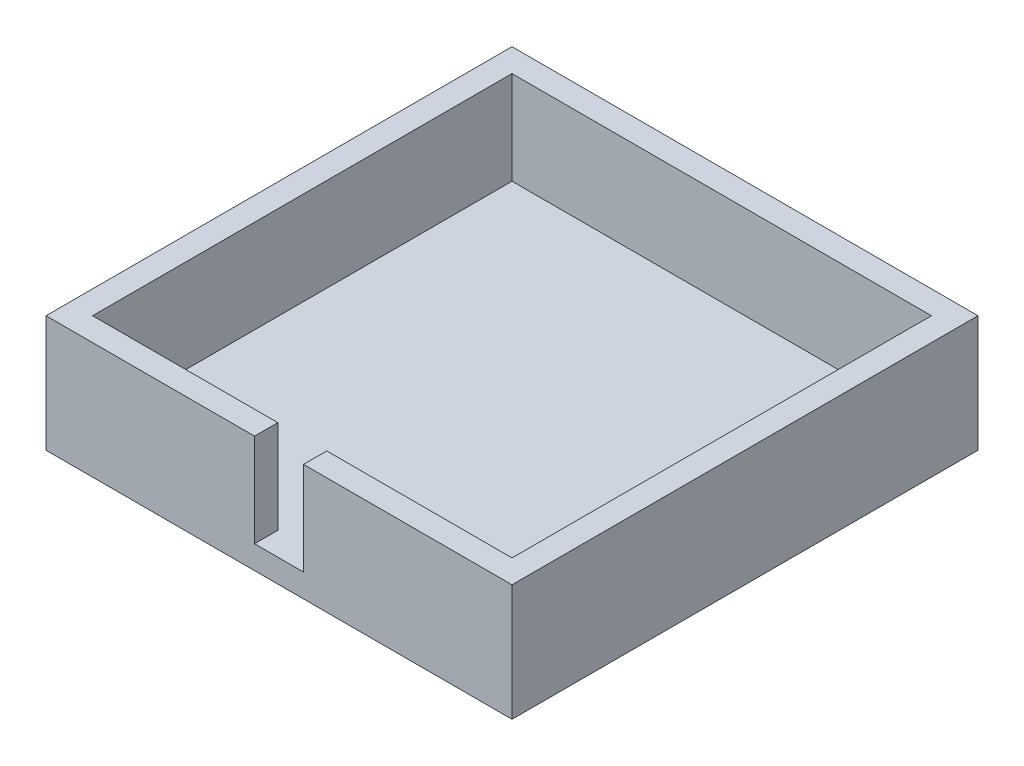
SolidWorks part; units mm, degrees
material "Plain Carbon Steel"
ref_plane "Front Plane" through (0, 0, 0) normal (0, 0, 1) x (1, 0, 0)
ref_plane "Top Plane" through (0, 0, 0) normal (0, 1, 0) x (1, 0, 0)
ref_plane "Right Plane" through (0, 0, 0) normal (1, 0, 0) x (0, 0, -1)
sketch "Sketch1" plane through (0, 0, 0) normal (0, 1, 0) x (1, 0, 0)
  line L1 (-100, -100) -> (100, -100)
  line L2 (-100, -100) -> (-100, 100)
  line L3 (-100, 100) -> (100, 100)
  line L4 (100, -100) -> (100, 100)
  line L5 (-100, -100) -> (100, 100) construction
  line L6 (-100, 100) -> (100, -100) construction
  point P0 (0, 0)
  dimension "D1" = 200
  dimension "D2" = 200
extrude "Boss-Extrude1" add sketch "Sketch1" along normal blind 50
sketch "Sketch2" plane through (0, 50, 0) normal (0, 1, 0) x (1, 0, 0)
  line L0 (100, 100) -> (-100, 100) construction
  line L1 (-90, -90) -> (90, -90)
  line L2 (-90, -90) -> (-90, 90)
  line L3 (-90, 90) -> (90, 90)
  line L4 (90, -90) -> (90, 90)
  line L5 (-90, -90) -> (90, 90) construction
  line L6 (-90, 90) -> (90, -90) construction
  line L7 (100, -100) -> (100, 100) construction
  point P0 (0, 0)
  dimension "D1" = 10
  dimension "D2" = 10
extrude "Cut-Extrude1" cut sketch "Sketch2" against normal blind 40 and the other way through all
sketch "Sketch3" plane through (0, 0, 100) normal (0, 0, 1) x (1, 0, 0)
  line L0 (-10.5, 10) -> (10.5, 10)
  line L1 (-10.5, 10) -> (-10.5, 50)
  line L2 (-100, 50) -> (100, 50) construction
  line L3 (10.5, 10) -> (10.5, 50)
  line L4 (10.5, 50) -> (-10.5, 50)
  line L5 (-100, 0) -> (100, 0) construction
  dimension "D1" = 21
  dimension "D2" = 10
extrude "Cut-Extrude2" cut sketch "Sketch3" against normal blind 40
